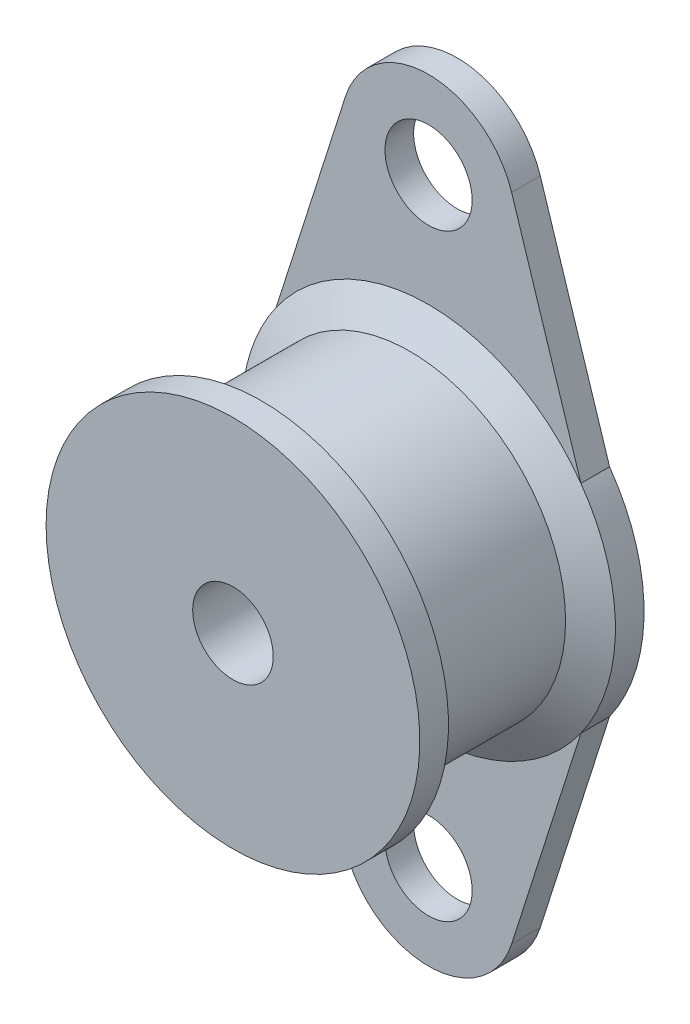
SolidWorks part; units mm, degrees
ref_plane "前视基准面" through (0, 0, 0) normal (0, 0, 1) x (1, 0, 0)
ref_plane "上视基准面" through (0, 0, 0) normal (0, 1, 0) x (1, 0, 0)
ref_plane "右视基准面" through (0, 0, 0) normal (1, 0, 0) x (0, 0, -1)
sketch "草图1" plane through (0, 0, 0) normal (0, 0, 1) x (1, 0, 0)
  line L0 (-12.2313, -8.6831) -> (-6.6692, -26.1266)
  line L1 (6.6692, -26.1266) -> (12.2313, -8.6831)
  line L2 (12.2313, 8.6831) -> (6.6692, 26.1266)
  line L3 (-6.6692, 26.1266) -> (-12.2313, 8.6831)
  arc A0 (-12.2313, 8.6831) -> (-12.2313, -8.6831) centre (0, 0) ccw
  arc A1 (-6.6692, -26.1266) -> (6.6692, -26.1266) centre (0, -24) ccw
  arc A2 (12.2313, -8.6831) -> (12.2313, 8.6831) centre (0, 0) ccw
  arc A3 (6.6692, 26.1266) -> (-6.6692, 26.1266) centre (0, 24) ccw
  circle A4 centre (0, -24) radius 3.5
  circle A5 centre (0, 24) radius 3.5
extrude "凸台-拉伸1" add sketch "草图1" along normal blind 2.3
sketch "草图2" plane through (0, 0, 0) normal (0, 1, 0) x (1, 0, 0)
  line L0 (0, -2.3) -> (15, -2.3)
  line L1 (15, -2.3) -> (12.5, -3.8)
  line L2 (12.5, -3.8) -> (12.5, -14.2)
  line L3 (12.5, -14.2) -> (15, -15.7)
  line L4 (15, -15.7) -> (0, -15.7)
  line L5 (0, -15.7) -> (0, -2.3)
  line L6 (0, -15.7) -> (0, -2.3) construction
revolve "旋转1" add sketch "草图2" angle 360 about L6
sketch "草图3" plane through (0, 0, 0) normal (0, 1, 0) x (1, 0, 0)
  line L0 (0, -15.7) -> (15, -15.7)
  line L1 (15, -15.7) -> (15, -18)
  line L2 (15, -18) -> (0, -18)
  line L3 (0, -18) -> (0, -15.7)
  line L4 (0, -18) -> (0, -15.7) construction
revolve "旋转2" add sketch "草图3" angle 360 about L4
sketch "草图4" plane through (0, 0, 0) normal (0, 1, 0) x (1, 0, 0)
  line L0 (0, -10.8) -> (4, -10.8)
  line L1 (4, -10.8) -> (3.233, -11.3)
  line L2 (3.233, -11.3) -> (3.233, -18)
  line L3 (3.233, -18) -> (0, -18)
  line L4 (0, -18) -> (0, -10.8)
  line L5 (0, -18) -> (0, -10.8) construction
revolve "切除-旋转1" cut sketch "草图4" angle 360 about L5
cosmetic thread "装饰螺纹线1" parameters "D1"=6.7, "D2"=8
